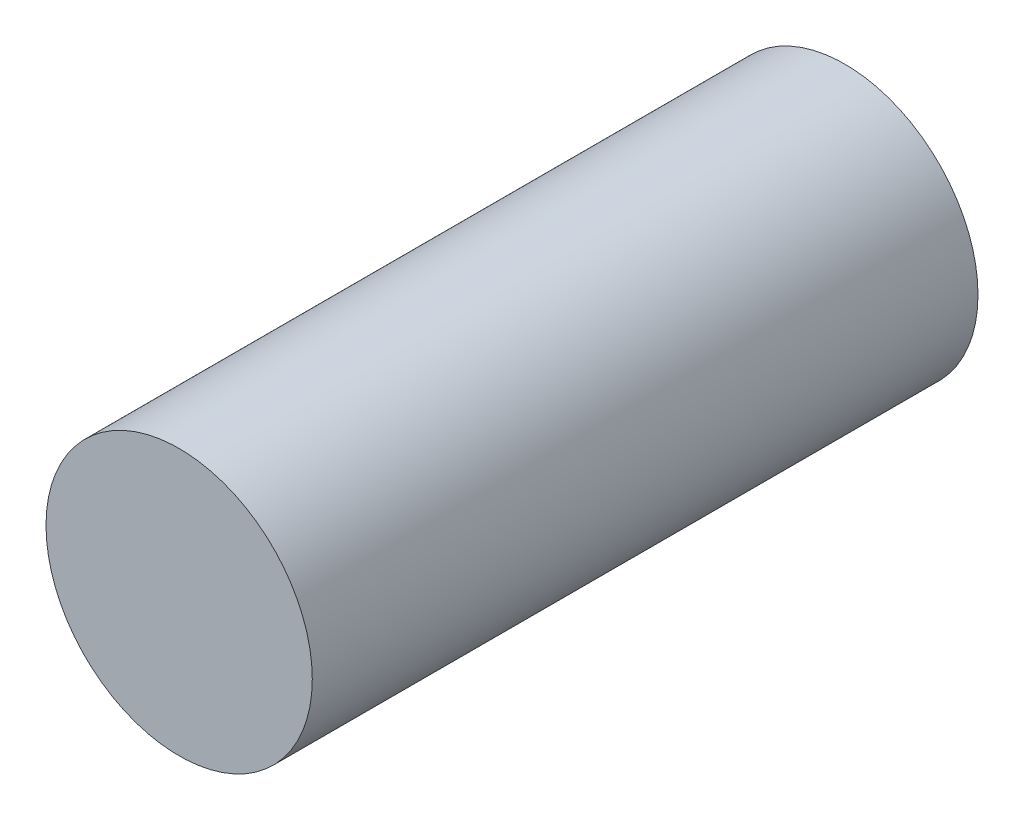
SolidWorks part; units mm, degrees
ref_plane "Alzado" through (0, 0, 0) normal (0, 0, 1) x (1, 0, 0)
ref_plane "Planta" through (0, 0, 0) normal (0, 1, 0) x (1, 0, 0)
ref_plane "Vista lateral" through (0, 0, 0) normal (1, 0, 0) x (0, 0, -1)
sketch "Croquis1" plane through (0, 0, 0) normal (0, 0, 1) x (1, 0, 0)
  circle A0 centre (0, 0) radius 6
  dimension "D1" = 12
extrude "Saliente-Extruir1" add sketch "Croquis1" along normal blind 30
